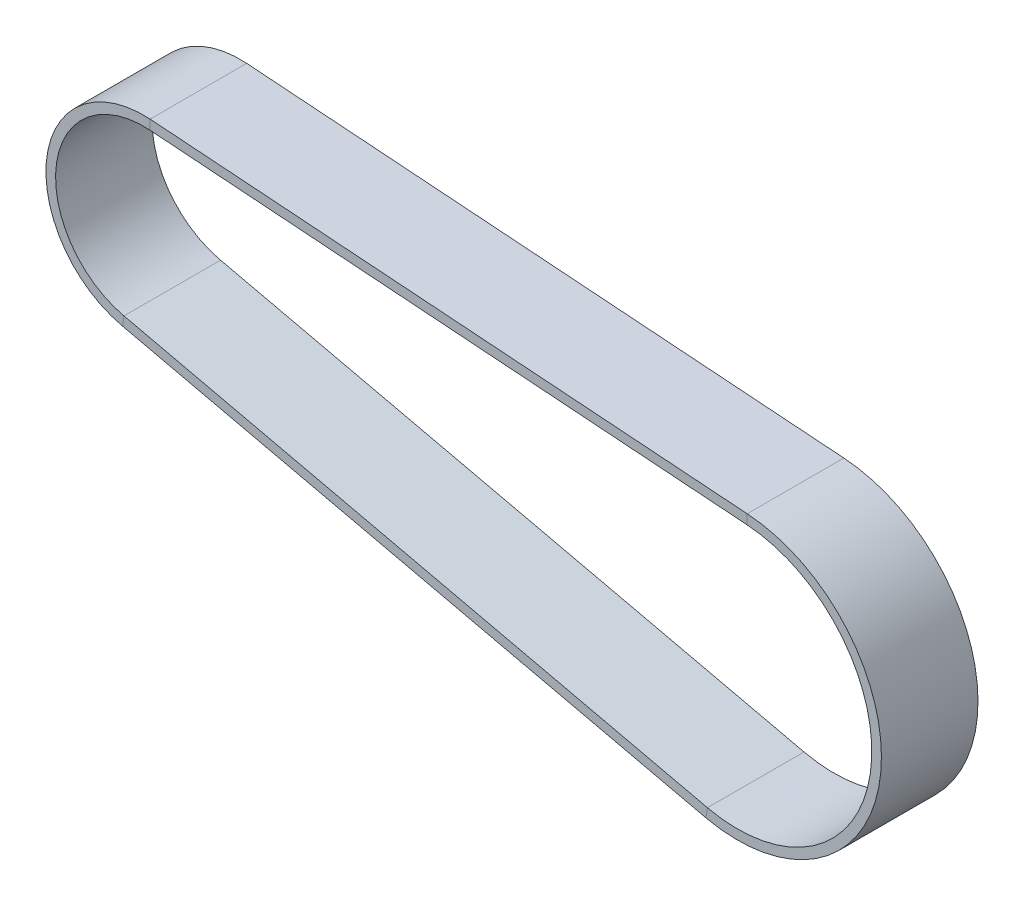
SolidWorks part; units mm, degrees
ref_plane "Alzado" through (0, 0, 0) normal (0, 0, 1) x (1, 0, 0)
ref_plane "Planta" through (0, 0, 0) normal (0, 1, 0) x (1, 0, 0)
ref_plane "Vista lateral" through (0, 0, 0) normal (1, 0, 0) x (0, 0, -1)
sketch "Croquis2" plane through (0, 0, 0) normal (0, 0, 1) x (1, 0, 0)
  line L0 (0, 0) -> (1, 0) construction
  line L1 (0, 0) -> (0, 1) construction
  line L2 (0.6594, 9.1062) -> (62.4915, 4.6287)
  line L3 (58.3709, -22.7913) -> (-2.0461, -8.8978)
  arc A0 (-2.0461, -8.8978) -> (0.6594, 9.1062) centre (0, 0) cw
  arc A1 (62.4915, 4.6287) -> (58.3709, -22.7913) centre (61.4872, -9.24) cw
ref_plane "Plano1" through (0.6594, 0, 0) normal (1, 0, 0) x (0, 0, -1)
sketch "Croquis3" plane through (0.6594, 0, 0) normal (1, 0, 0) x (0, 0, -1)
  line L1 (-5, 10.1062) -> (5, 10.1062)
  line L2 (-5, 10.1062) -> (-5, 9.1062)
  line L3 (-5, 9.1062) -> (5, 9.1062)
  line L4 (5, 10.1062) -> (5, 9.1062)
  point P4 (0, 9.1062)
  dimension "D1" = 1
  dimension "D2" = 10
sweep "Barrer1" add profiles "Croquis3" path "Croquis2"
